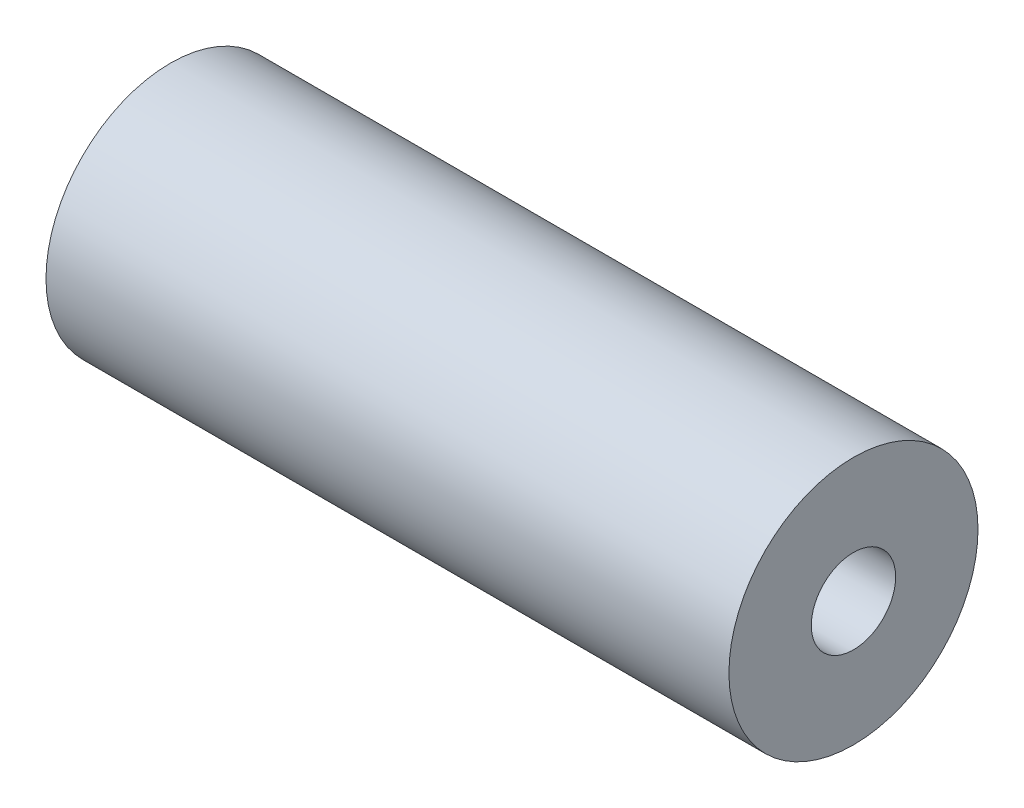
SolidWorks part; units mm, degrees
ref_plane "前视基准面" through (0, 0, 0) normal (0, 0, 1) x (1, 0, 0)
ref_plane "上视基准面" through (0, 0, 0) normal (0, 1, 0) x (1, 0, 0)
ref_plane "右视基准面" through (0, 0, 0) normal (1, 0, 0) x (0, 0, -1)
sketch "草图2" plane through (0, 0, 0) normal (1, 0, 0) x (0, 0, -1)
  circle A0 centre (0, 0) radius 31
  dimension "D1" = 62
extrude "凸台-拉伸1" add sketch "草图2" along normal blind 170
sketch "草图4" plane through (170, 0, 0) normal (1, 0, 0) x (0, 0, -1)
  point P0 (0, 0)
hole_wizard "M24 螺纹孔1" positions "草图4" profile "草图5" tap size "M24" standard "GB"
sketch "草图5" plane through (170, 0, 0) normal (0, 1, 0) x (0, 0, -1)
  line L0 (0, 0) -> (0, 46.309)
  line L1 (0, 46.309) -> (10.5, 40)
  line L2 (10.5, 40) -> (10.5, 0)
  line L5 (10.5, 0) -> (0, 0)
  line L10 (0, 46.309) -> (-10.5, 40) construction
  line L11 (0, -6.35) -> (0, 107.95) construction
  dimension "螺纹孔钻头直径" = 21
  dimension "螺纹孔钻头深度" = 40
  dimension "导头角度" = 118
cosmetic thread "孔螺纹线1" parameters "D1"=40, "D2"=24
sketch "草图6" plane through (170, 0, 0) normal (1, 0, 0) x (0, 0, -1)
  circle A0 centre (0, 0) radius 15
  dimension "D1" = 30
extrude "切除-拉伸1" cut sketch "草图6" against normal blind 54 from offset 40 offset against normal yes
sketch "草图7" plane through (0, 0, 0) normal (0, 0, 1) x (1, 0, 0)
  line L0 (0, 0) -> (76, 0)
  line L1 (76, -15) -> (76, 15) construction
  line L2 (76, 0) -> (76, 10)
  line L3 (76, 10) -> (0, 13.8)
  line L4 (0, 31) -> (0, -31) construction
  line L5 (0, 13.8) -> (0, 0)
  line L6 (76, 10) -> (56, 10) construction
  line L7 (56, 10) -> (56, 11) construction
  line L8 (76, 0) -> (97.84, 0) construction
  dimension "D1" = 10
  dimension "D2" = 20
  dimension "D3" = 1
revolve "切除-旋转1" cut sketch "草图7" angle 360 about L8
sketch "草图8" plane through (0, 0, 0) normal (0, 1, 0) x (1, 0, 0)
  line L0 (25, 0) -> (83, 0) construction
  line L1 (25, 5) -> (83, 5)
  line L2 (25, -5) -> (83, -5)
  arc A0 (25, 5) -> (25, -5) centre (25, 0) ccw
  arc A1 (83, -5) -> (83, 5) centre (83, 0) ccw
  point P3 (54, 0)
  point P8 (54, 0)
  point P9 (83, -9.4876)
  dimension "D1" = 58
  dimension "D2" = 25
  dimension "D3" = 10
extrude "切除-拉伸2" cut sketch "草图8" against normal through all from offset 25
